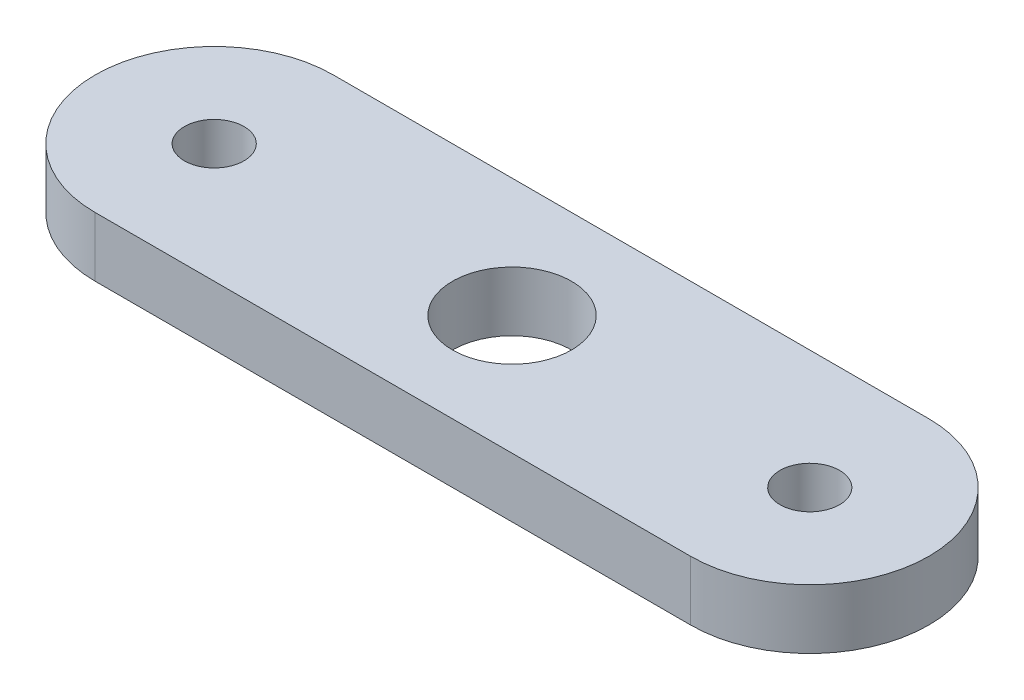
SolidWorks part; units mm, degrees
ref_plane "Front Plane" through (0, 0, 0) normal (0, 0, 1) x (1, 0, 0)
ref_plane "Top Plane" through (0, 0, 0) normal (0, 1, 0) x (1, 0, 0)
ref_plane "Right Plane" through (0, 0, 0) normal (1, 0, 0) x (0, 0, -1)
sketch "Sketch2" plane through (0, 0, 0) normal (0, 1, 0) x (1, 0, 0)
  line L0 (-50, 0) -> (50, 0) construction
  line L1 (-50, 20) -> (50, 20)
  line L2 (-50, -20) -> (50, -20)
  arc A0 (-50, 20) -> (-50, -20) centre (-50, 0) ccw
  arc A1 (50, -20) -> (50, 20) centre (50, 0) ccw
  circle A2 centre (50, 0) radius 5
  circle A3 centre (-50, 0) radius 5
  circle A4 centre (0, 0) radius 10
  point P2 (0, 0)
  dimension "D2" = 20
  dimension "D3" = 10
  dimension "D4" = 10
  dimension "D5" = 20
  dimension "D1" = 100
extrude "Boss-Extrude1" add sketch "Sketch2" along normal blind 10
sketch "Sketch3" plane through (0, 0, 0) normal (0, 0, 1) x (1, 0, 0)
  line L0 (0, 0) -> (0, 49.6308) construction
scale "Scale2" scale about centroid uniform scaling yes scale factor 0.2004
